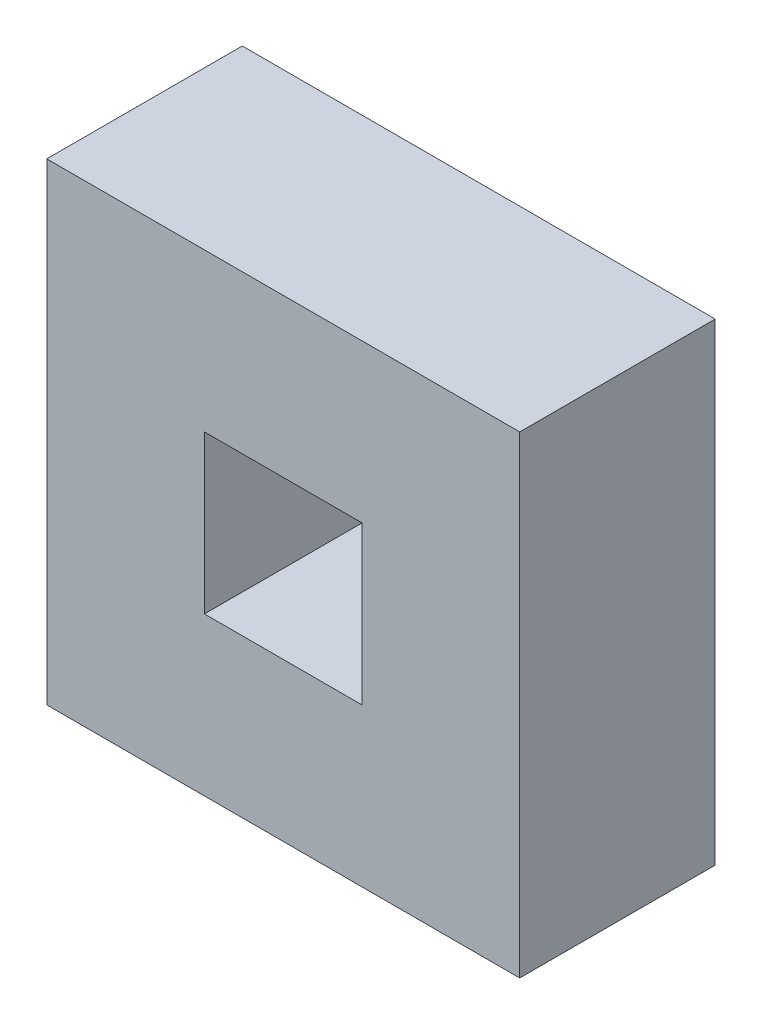
SolidWorks part; units mm, degrees
ref_plane "Front" through (0, 0, 0) normal (0, 0, 1) x (1, 0, 0)
ref_plane "Top" through (0, 0, 0) normal (0, 1, 0) x (1, 0, 0)
ref_plane "Right" through (0, 0, 0) normal (1, 0, 0) x (0, 0, -1)
sketch "Sketch1" plane through (0, 0, 0) normal (0, 0, 1) x (1, 0, 0)
  line L1 (0, 0) -> (30, 0)
  line L2 (0, 0) -> (0, 30)
  line L3 (0, 30) -> (30, 30)
  line L4 (30, 0) -> (30, 30)
  line L5 (10, 20) -> (20, 20)
  line L6 (10, 20) -> (10, 10)
  line L7 (10, 10) -> (20, 10)
  line L8 (20, 20) -> (20, 10)
  dimension "D1" = 30
  dimension "D2" = 30
  dimension "D3" = 10
  dimension "D4" = 10
  dimension "D5" = 10
  dimension "D6" = 10
extrude "Boss-Extrude1" add sketch "Sketch1" along normal blind 12.4
